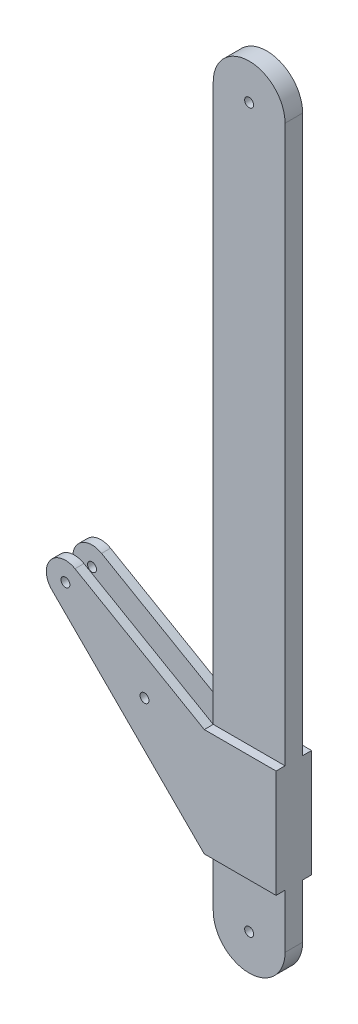
SolidWorks part; units mm, degrees
material "1060 Alloy"
ref_plane "Front Plane" through (0, 0, 0) normal (0, 0, 1) x (1, 0, 0)
ref_plane "Top Plane" through (0, 0, 0) normal (0, 1, 0) x (1, 0, 0)
ref_plane "Right Plane" through (0, 0, 0) normal (1, 0, 0) x (0, 0, -1)
sketch "Sketch1" plane through (0, 0, 0) normal (0, 0, 1) x (1, 0, 0)
  line L1 (-1.25, -100) -> (1.25, -100)
  line L2 (-10, -100) -> (-10, 100)
  line L4 (10, -100) -> (10, 100)
  line L5 (-10, -100) -> (10, 100) construction
  line L6 (-10, 100) -> (10, -100) construction
  arc A0 (10, 100) -> (-10, 100) centre (0, 100) ccw
  arc A1 (-10, -100) -> (10, -100) centre (0, -100) ccw
  circle A2 centre (0, -100) radius 1.25
  circle A3 centre (0, 100) radius 1.25
  point P0 (0, 0)
  dimension "D3" = 2.5
  dimension "D4" = 2.5
  dimension "D1" = 200
  dimension "D2" = 20
extrude "Boss-Extrude2" add sketch "Sketch1" along normal mid plane 4.9 contours L2 A1 L4 A0 A3 A2
ref_point "Point2"
ref_point "Point3"
sketch "Sketch4" plane through (0, 0, 2.45) normal (0, 0, 1) x (1, 0, 0)
  line L0 (-10, -85) -> (-52.4264, -42.5736)
  line L1 (-10, -100) -> (-10, 100) construction
  line L2 (-52.8849, -35.5779) -> (-48.6672, -38.8143) construction
  line L3 (-46.009, -34.2102) -> (-10, -55)
  line L4 (-10, -55) -> (10, -55)
  line L5 (10, -100) -> (10, 100) construction
  line L6 (10, -55) -> (10, -85)
  line L7 (10, -85) -> (-10, -85)
  arc A0 (-46.009, -34.2102) -> (-52.4264, -42.5736) centre (-48.6672, -38.8143) ccw
  circle A2 centre (-48.6672, -38.8143) radius 1.25
  circle A3 centre (0, -100) radius 1.25 construction
  circle A4 centre (-26.6456, -55.712) radius 1.25
  dimension "D2" = 45
  dimension "D5" = 2.5
  dimension "D7" = 2.5
  dimension "D1" = 60
  dimension "D3" = 45
  dimension "D4" = 60
  dimension "D6" = 30
extrude "Boss-Extrude4" add sketch "Sketch4" along normal blind 2.5
mirror "Mirror1" about plane through (0, 0, 0) normal (0, 0, 1) of "Boss-Extrude4"
